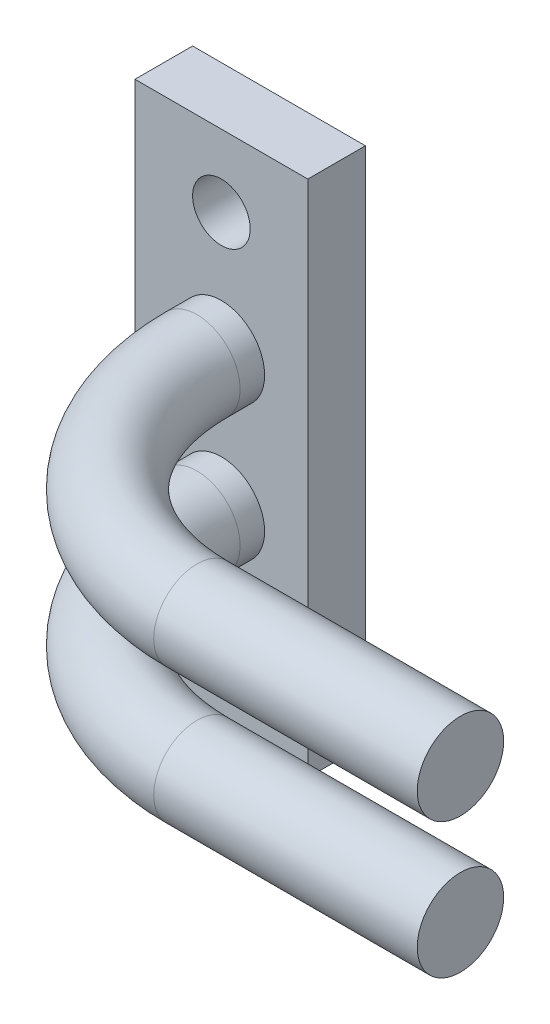
SolidWorks part; units mm, degrees
ref_plane "Front Plane" through (0, 0, 0) normal (0, 0, 1) x (1, 0, 0)
ref_plane "Top Plane" through (0, 0, 0) normal (0, 1, 0) x (1, 0, 0)
ref_plane "Right Plane" through (0, 0, 0) normal (1, 0, 0) x (0, 0, -1)
sketch "Sketch1" plane through (0, 0, 0) normal (0, 0, 1) x (1, 0, 0)
  line L1 (-3, -9) -> (3, -9)
  line L2 (-3, -9) -> (-3, 9)
  line L3 (-3, 9) -> (3, 9)
  line L4 (3, -9) -> (3, 9)
  line L5 (-3, -9) -> (3, 9) construction
  line L6 (-3, 9) -> (3, -9) construction
  point P0 (0, 0)
  dimension "D1" = 18
  dimension "D2" = 6
extrude "Boss-Extrude1" add sketch "Sketch1" along normal blind 2
sketch "Sketch2" plane through (0, 0, 0) normal (0, 0, -1) x (-1, 0, 0)
  circle A0 centre (0, 2.35) radius 1.5
  circle A1 centre (0, -2.35) radius 1.5
  dimension "D2" = 3
  dimension "D1" = 4.7
  dimension "D3" = 2.35
extrude "Boss-Extrude2" add sketch "Sketch2" along normal blind 2.1
fillet "Fillet1" radius 1.5 2 edges at (-1.5, -2.35, -2.1) (-1.5, 2.35, -2.1)
sketch "Sketch3" plane through (0, 0, 2) normal (0, 0, 1) x (1, 0, 0)
  circle A0 centre (0, -2.35) radius 1.5 construction
  circle A1 centre (0, 2.35) radius 1.5 construction
  circle A2 centre (0, -2.35) radius 1.5
  circle A3 centre (0, 2.35) radius 1.5
ref_plane "Plane1" through (0, 2.35, 0) normal (0, 1, 0) x (-1, 0, 0)
sketch "Sketch4" plane through (0, 2.35, 0) normal (0, 1, 0) x (-1, 0, 0)
  line L0 (0, 2) -> (0, 2.85)
  line L1 (1.5, 2) -> (-1.5, 2) construction
  line L2 (-7.5, 10.35) -> (-16.65, 10.35)
  arc A0 (0, 2.85) -> (-7.5, 10.35) centre (-7.5, 2.85) ccw
  point P8 (0, 10.35)
  dimension "D3" = 7.5
  dimension "D1" = 16.65
  dimension "D2" = 8.35
sweep "Sweep1" add profiles "Sketch3" path "Sketch4"
sketch "Sketch5" plane through (0, 0, 2) normal (0, 0, 1) x (1, 0, 0)
  line L0 (0, 0) -> (0, 6.5) construction
  line L1 (0, 0) -> (3, 0) construction
  line L2 (3, -9) -> (3, 9) construction
  line L3 (3, 9) -> (-3, 9) construction
  circle A0 centre (0, 6.5) radius 1
  circle A1 centre (0, -6.5) radius 1
  dimension "D1" = 2
  dimension "D2" = 2.5
extrude "Cut-Extrude1" cut sketch "Sketch5" against normal through all
